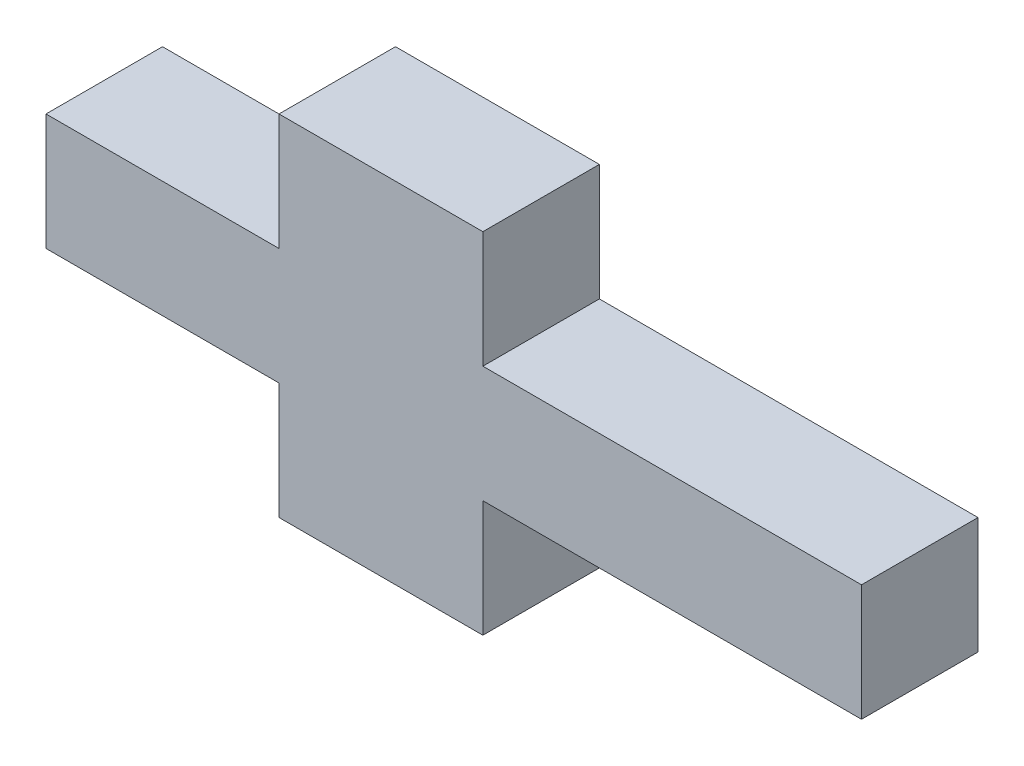
SolidWorks part; units mm, degrees
ref_plane "Piano frontale" through (0, 0, 0) normal (0, 0, 1) x (1, 0, 0)
ref_plane "Piano superiore" through (0, 0, 0) normal (0, 1, 0) x (1, 0, 0)
ref_plane "Piano destro" through (0, 0, 0) normal (1, 0, 0) x (0, 0, -1)
sketch "Schizzo1" plane through (0, 0, 0) normal (0, 0, 1) x (1, 0, 0)
  line L0 (0, 0) -> (0, 4)
  line L2 (8, 4) -> (8, 8)
  line L3 (8, 8) -> (15, 8)
  line L4 (15, 8) -> (15, 4)
  line L5 (15, 4) -> (28, 4)
  line L6 (28, 4) -> (28, 0)
  line L7 (28, 0) -> (15, 0)
  line L8 (15, 0) -> (15, -4)
  line L9 (15, -4) -> (8, -4)
  line L10 (8, -4) -> (8, 0)
  line L11 (8, 0) -> (0, 0)
  line L17 (0, 4) -> (8, 4)
  point P12 (0, 0)
  point P14 (0, 0)
  point P15 (15, 1.8547)
  point P16 (3.0216, 4)
  point P17 (-0.0438, 4)
  dimension "D1" = 4
  dimension "D2" = 8
  dimension "D3" = 7
  dimension "D4" = 4
  dimension "D5" = 4
  dimension "D6" = 28
extrude "Estrusione-Estrusione1" add sketch "Schizzo1" along normal blind 4
